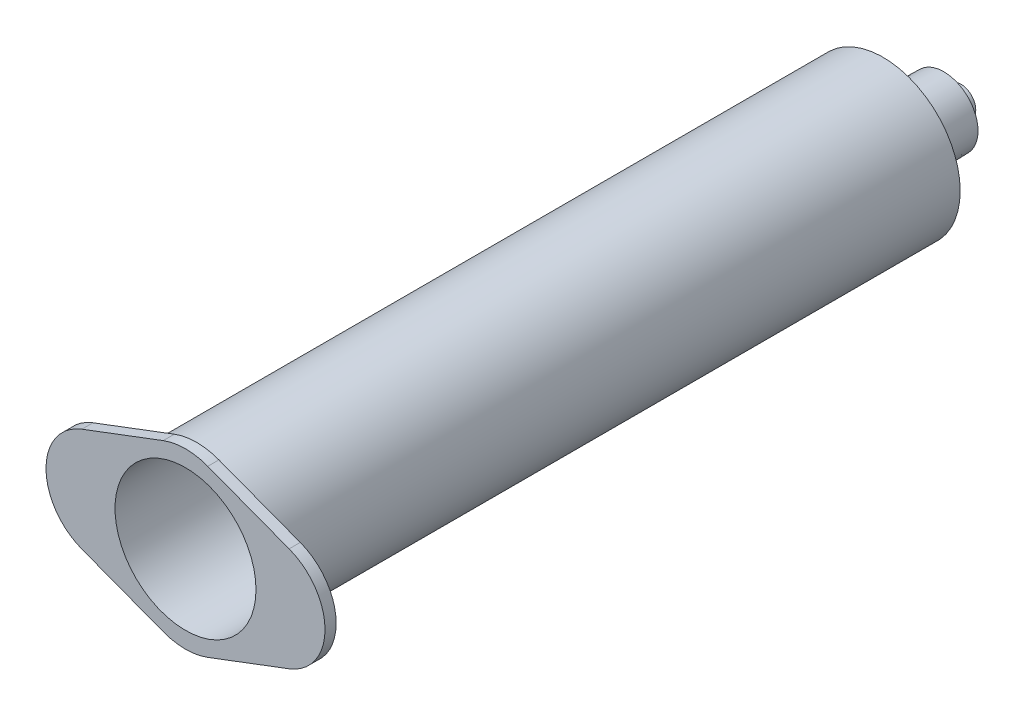
SolidWorks part; units mm, degrees
ref_plane "Front Plane" through (0, 0, 0) normal (0, 0, 1) x (1, 0, 0)
ref_plane "Top Plane" through (0, 0, 0) normal (0, 1, 0) x (1, 0, 0)
ref_plane "Right Plane" through (0, 0, 0) normal (1, 0, 0) x (0, 0, -1)
sketch "Sketch1" plane through (0, 0, 0) normal (0, 0, 1) x (1, 0, 0)
  circle A0 centre (0, 0) radius 9.5
  circle A1 centre (0, 0) radius 10.4
  dimension "D1" = 20.8
  dimension "D2" = 19
extrude "Boss-Extrude1" add sketch "Sketch1" along normal blind 92.5
sketch "Sketch2" plane through (0, 0, 0) normal (1, 0, 0) x (0, 0, -1)
  line L0 (0, 0) -> (12.896, 0) construction
  line L1 (0, 10.4) -> (1.2, 4.8)
  line L2 (1.2, 4.8) -> (8.2, 4.6)
  line L3 (8.2, 4.6) -> (8.2, 3.8)
  line L4 (8.2, 3.8) -> (2.2, 3.8)
  line L5 (2.2, 3.8) -> (2.2, 2)
  line L6 (2.2, 2) -> (10.5, 2)
  line L7 (10.5, 2) -> (10.5, 0.97)
  line L8 (10.5, 0.97) -> (1.2, 0.97)
  line L9 (1.2, 0.97) -> (1.2, 3.9)
  line L10 (1.2, 3.9) -> (0, 9.5)
  line L11 (0, 9.5) -> (0, 10.4)
  dimension "D1" = 1.94
  dimension "D2" = 4
  dimension "D3" = 9.2
  dimension "D4" = 9.6
  dimension "D5" = 7
  dimension "D6" = 2.3
  dimension "D7" = 1.2
  dimension "D8" = 6
  dimension "D9" = 0.8
  dimension "D10" = 77.905
revolve "Revolve1" add sketch "Sketch2" angle 360 about L0
sketch "Sketch3" plane through (0, 0, 92.5) normal (0, 0, 1) x (1, 0, 0)
  line L0 (0, 11.7) -> (0, 0) construction
  line L1 (0, 0) -> (-18.8, 0) construction
  line L2 (-3, 11.1511) -> (-13.9652, 7)
  line L3 (-3, -11.1511) -> (-13.9652, -7)
  line L4 (3, -11.1511) -> (13.9652, -7)
  line L5 (3, 11.1511) -> (13.9652, 7)
  circle A0 centre (0, 0) radius 9.5 construction
  circle A1 centre (0, 0) radius 9.5
  arc A2 (-13.9652, -7) -> (-13.9652, 7) centre (-11.3152, 0) cw
  arc A3 (3, 11.1511) -> (-3, 11.1511) centre (0, 3.2267) ccw
  arc A4 (3, -11.1511) -> (-3, -11.1511) centre (0, -3.2267) cw
  arc A5 (13.9652, -7) -> (13.9652, 7) centre (11.3152, 0) ccw
  point P9 (-9.5, 0)
  point P11 (0, 9.5)
  dimension "D5" = 19
  dimension "D1" = 2.2
  dimension "D2" = 9.3
  dimension "D3" = 14
  dimension "D4" = 6
extrude "Boss-Extrude2" add sketch "Sketch3" along normal blind 1.5
